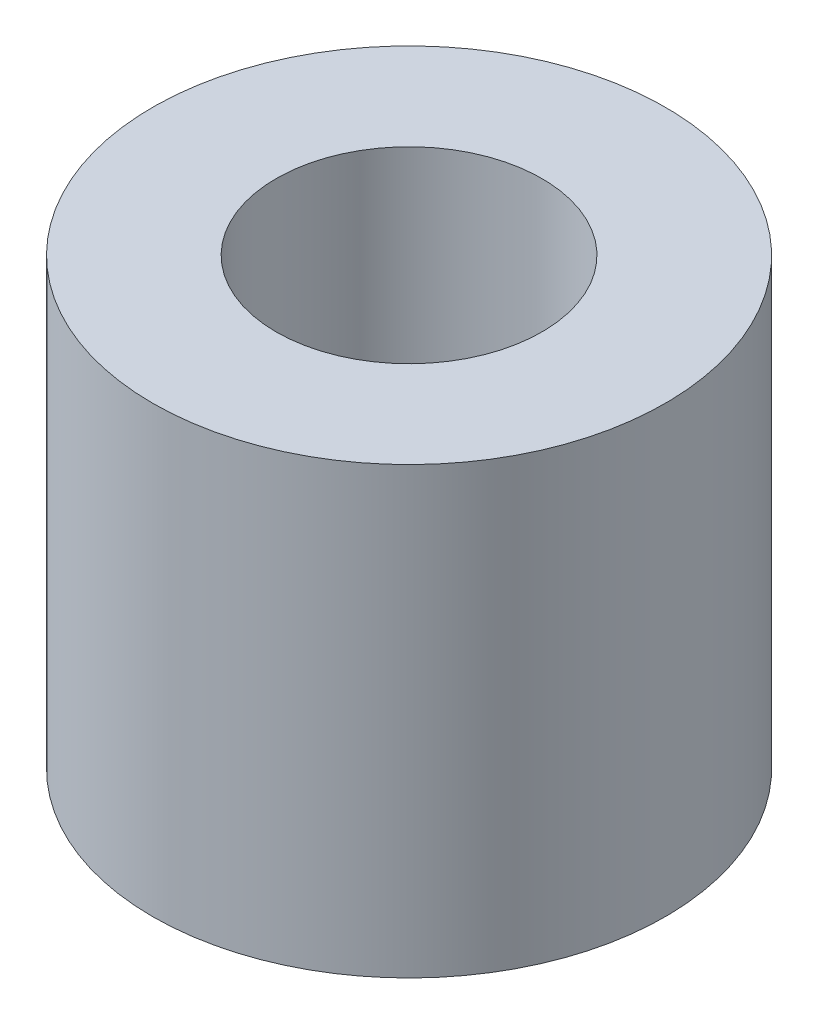
SolidWorks part; units mm, degrees
ref_plane "Front Plane" through (0, 0, 0) normal (0, 0, 1) x (1, 0, 0)
ref_plane "Top Plane" through (0, 0, 0) normal (0, 1, 0) x (1, 0, 0)
ref_plane "Right Plane" through (0, 0, 0) normal (1, 0, 0) x (0, 0, -1)
sketch "Sketch1" plane through (0, 0, 0) normal (0, 1, 0) x (1, 0, 0)
  circle A0 centre (0, 0) radius 2.0574
  circle A1 centre (0, 0) radius 3.9688
  dimension "D1" = 4.1148
  dimension "D2" = 7.9375
extrude "Boss-Extrude1" add sketch "Sketch1" along normal blind 6.8834
